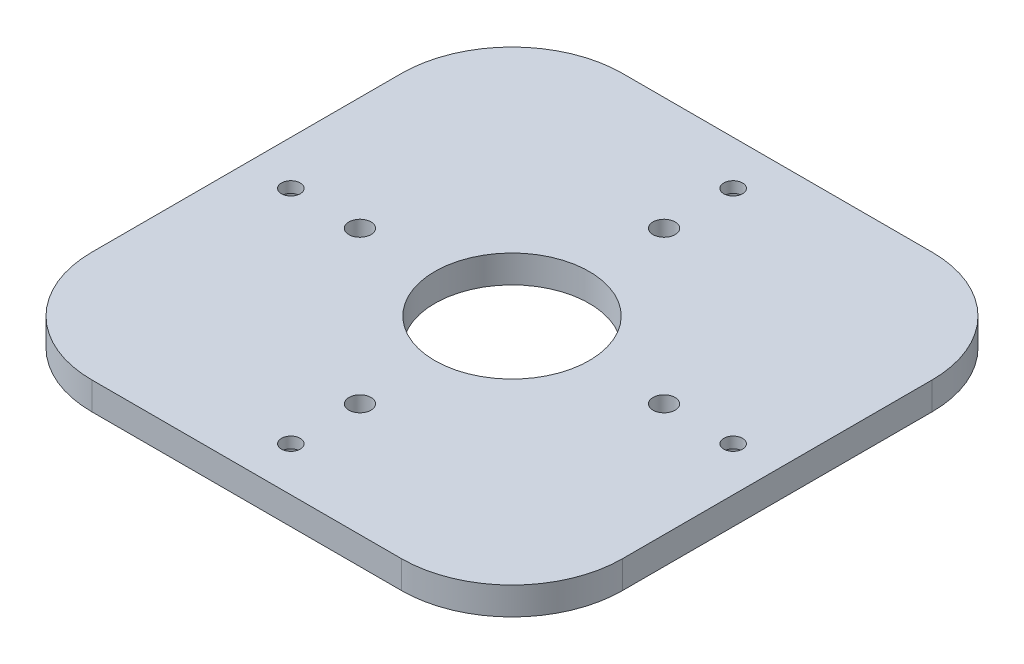
SolidWorks part; units mm, degrees
material "PET"
ref_plane "Front Plane" through (0, 0, 0) normal (0, 0, 1) x (1, 0, 0)
ref_plane "Top Plane" through (0, 0, 0) normal (0, 1, 0) x (1, 0, 0)
ref_plane "Right Plane" through (0, 0, 0) normal (1, 0, 0) x (0, 0, -1)
sketch "Sketch1" plane through (0, 0, 0) normal (0, 1, 0) x (1, 0, 0)
  line L0 (0, 0) -> (-48, 0) construction
  line L1 (-48, 48) -> (48, 48)
  line L2 (-48, 48) -> (-48, -48)
  line L3 (-48, -48) -> (48, -48)
  line L4 (48, 48) -> (48, -48)
  line L7 (0, 0) -> (0, 48) construction
  circle A4 centre (0, 0) radius 13.97
  point P4 (48, 0)
  point P6 (0, 48)
  dimension "D3" = 27.94
extrude "Boss-Extrude1" add sketch "Sketch1" along normal blind 5
fillet "Fillet1" radius 20 4 edges at (-48, 2.5, -48) (48, 2.5, -48) (48, 2.5, 48) (-48, 2.5, 48)
sketch "Sketch4" plane through (0, 0, 0) normal (0, -1, 0) x (1, 0, 0)
  line L0 (0, 40) -> (0, -40) construction
  line L1 (-40, 0) -> (40, 0) construction
  circle A0 centre (0, 0) radius 40 construction
  dimension "D1" = 80
hole_wizard "CBORE for M3 SHCS1" positions "3DSketch2" profile "Sketch6" counterbore size "M3" standard "ANSI Metric" end condition through all
sketch3d "3DSketch2"
  point P0 (-40, 0, 0)
  point P3 (0, 0, 40)
  point P6 (40, 0, 0)
  point P9 (0, 0, -40)
sketch "Sketch6" plane through (-40, 0, 0) normal (1, 0, 0) x (0, 0, -1)
  line L0 (0, 0) -> (0, 5)
  line L1 (0, 5) -> (1.7, 5)
  line L3 (1.7, 5) -> (1.7, 3)
  line L4 (3.25, 3) -> (1.7, 3)
  line L5 (3.25, 3) -> (3.25, 0.025)
  line L6 (3.25, 0.025) -> (3.275, 0)
  line L7 (3.275, 0) -> (0, 0)
  line L8 (-3.25, 0.025) -> (-3.275, 0) construction
  line L11 (0, -6.35) -> (0, 107.95) construction
  dimension "Thru Hole Dia." = 3.4
  dimension "Thru Hole Depth" = 5
  dimension "C'Bore Dia." = 6.5
  dimension "C'Bore Depth" = 3
  dimension "Near C'Sink Dia." = 6.55
  dimension "Near C'Sink Angle" = 90
sketch "Sketch7" plane through (0, 0, 0) normal (0, -1, 0) x (1, 0, 0)
  line L0 (0, 27.5) -> (0, -27.5) construction
  line L1 (-27.5, 0) -> (27.5, 0) construction
  circle A0 centre (-27.5, 0) radius 2
  circle A1 centre (0, 27.5) radius 2
  circle A2 centre (27.5, 0) radius 2
  circle A3 centre (0, -27.5) radius 2
  point P5 (0, 0)
  point P6 (0, 0)
  point P8 (0, 0)
  point P17 (0, 0)
  dimension "D2" = 4
  dimension "D1" = 55
  dimension "D3" = 4
extrude "Cut-Extrude1" cut sketch "Sketch7" against normal through all
